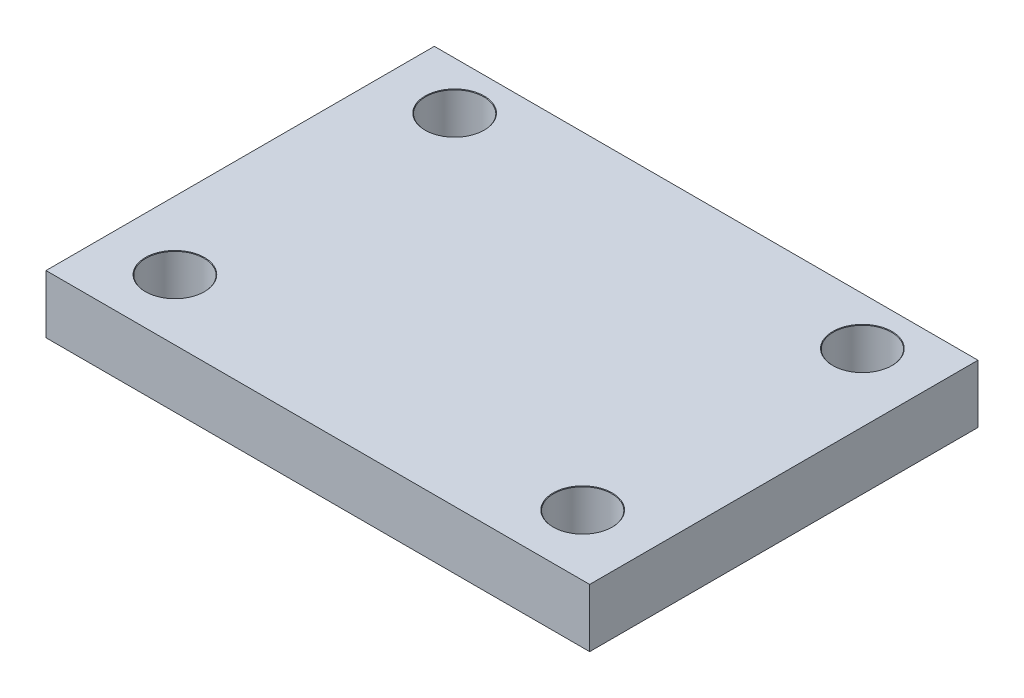
SolidWorks part; units mm, degrees
ref_plane "Front Plane" through (0, 0, 0) normal (0, 0, 1) x (1, 0, 0)
ref_plane "Top Plane" through (0, 0, 0) normal (0, 1, 0) x (1, 0, 0)
ref_plane "Right Plane" through (0, 0, 0) normal (1, 0, 0) x (0, 0, -1)
sketch "Sketch1" plane through (0, 0, 0) normal (0, 1, 0) x (1, 0, 0)
  line L1 (-14, -10) -> (14, -10)
  line L2 (-14, -10) -> (-14, 10)
  line L3 (-14, 10) -> (14, 10)
  line L4 (14, -10) -> (14, 10)
  line L5 (-14, -10) -> (14, 10) construction
  line L6 (-14, 10) -> (14, -10) construction
  point P0 (0, 0)
  dimension "D1" = 20
  dimension "D2" = 28
extrude "Boss-Extrude1" add sketch "Sketch1" against normal blind 3
sketch "Sketch2" plane through (0, 0, 0) normal (0, 1, 0) x (1, 0, 0)
  circle A1 centre (10.5, 7.5456) radius 1.3937
  circle A2 centre (10.5, -6.8605) radius 1.3937
  circle A3 centre (-10.5, -6.8605) radius 1.3937
  circle A4 centre (-10.5, 7.5456) radius 1.5
  point P14 (0, 0)
  dimension "D1" = 3
sketch "Sketch9" plane through (0, 0, 0) normal (0, 1, 0) x (1, 0, 0)
  point P0 (-10.5, 7.5456)
  point P3 (10.5, 7.5456)
  point P6 (10.5, -6.8605)
  point P9 (-10.5, -6.8605)
sketch "Sketch11" plane through (0, 0, 0) normal (0, 1, 0) x (1, 0, 0)
  point P0 (-10.5, 7.5456)
  point P3 (10.5, 7.5456)
  point P6 (10.5, -6.8605)
  point P9 (-10.5, -6.8605)
hole_wizard "Ø3.0 (3) Diameter Hole7" positions "Sketch11" profile "Sketch12" hole size "Ø3.0" standard "ANSI Metric"
sketch "Sketch12" plane through (-10.5, 0, -7.5456) normal (1, 0, 0) x (0, 0, 1)
  line L0 (0, 0) -> (0, 3.9013)
  line L1 (0, 3.9013) -> (1.5, 3)
  line L2 (1.5, 3) -> (1.5, 0.025)
  line L3 (1.5, 0.025) -> (1.525, 0)
  line L5 (1.525, 0) -> (0, 0)
  line L6 (-1.5, 0.025) -> (-1.525, 0) construction
  line L10 (0, 3.9013) -> (-1.5, 3) construction
  line L11 (0, -6.35) -> (0, 107.95) construction
  dimension "Hole Dia." = 3
  dimension "Hole Depth" = 3
  dimension "Near C'Sink Dia." = 3.05
  dimension "Near C'Sink Angle" = 90
  dimension "Drill Angle" = 118
cosmetic thread "Cosmetic Thread1" parameters "D2"=4
cosmetic thread "Cosmetic Thread2" parameters "D2"=4
cosmetic thread "Cosmetic Thread3" parameters "D2"=4
cosmetic thread "Cosmetic Thread4" parameters "D2"=4
